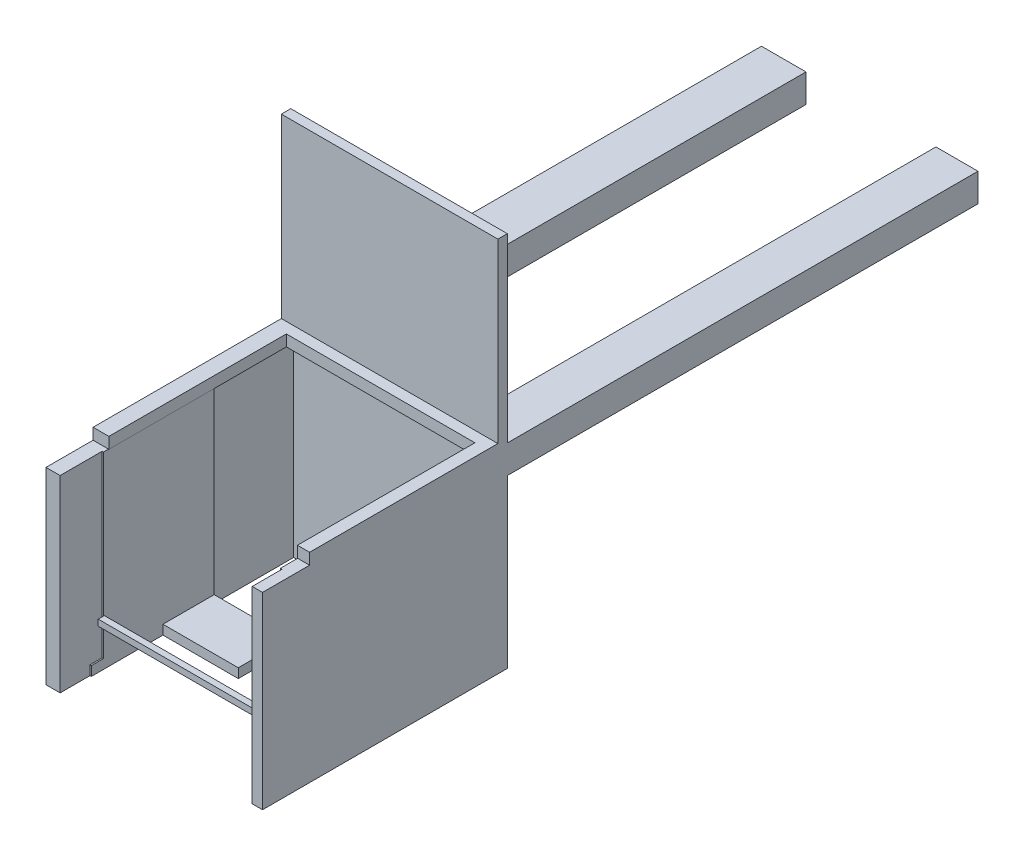
SolidWorks part; units mm, degrees
ref_plane "前视基准面" through (0, 0, 0) normal (0, 0, 1) x (1, 0, 0)
ref_plane "上视基准面" through (0, 0, 0) normal (0, 1, 0) x (1, 0, 0)
ref_plane "右视基准面" through (0, 0, 0) normal (1, 0, 0) x (0, 0, -1)
sketch "草图1" plane through (0, 0, 0) normal (1, 0, 0) x (0, 0, -1)
  line L1 (79.0349, 50.7103) -> (69.0349, 50.7103)
  line L2 (79.0349, 50.7103) -> (79.0349, -149.2897)
  line L3 (79.0349, -149.2897) -> (69.0349, -149.2897)
  line L4 (69.0349, 50.7103) -> (69.0349, -149.2897)
extrude "凸台-拉伸1" add sketch "草图1" along normal blind 230
ref_plane "基准面1" through (0, -149.2897, -69.0349) normal (-1, 0, 0) x (0, 0, 1)
sketch "草图3" plane through (0, -149.2897, 0) normal (0, -1, 0) x (1, 0, 0)
  line L0 (0, -5.7849) -> (0, -132.2849) construction
  line L1 (0, -69.0349) -> (230, -69.0349)
  line L2 (0, -69.0349) -> (0, -79.0349)
  line L3 (0, -79.0349) -> (230, -79.0349)
  line L4 (230, -69.0349) -> (230, -79.0349)
  line L5 (230, -69.0349) -> (0, -69.0349) construction
extrude "凸台-拉伸2" add sketch "草图3" along normal blind 200
sketch "草图4" plane through (0, 0, -69.0349) normal (0, 0, 1) x (1, 0, 0)
  line L0 (230, 50.7103) -> (230, -349.2897) construction
  line L1 (0, -349.2897) -> (230, -349.2897)
  line L2 (0, -349.2897) -> (0, -149.2897)
  line L3 (0, -149.2897) -> (230, -149.2897)
  line L4 (230, -349.2897) -> (230, -149.2897)
extrude "凸台-拉伸3" add sketch "草图4" along normal blind 250
sketch "草图5" plane through (0, 0, -79.0349) normal (0, 0, -1) x (-1, 0, 0)
  line L0 (0, -349.2897) -> (0, 50.7103) construction
  line L1 (0, -82.9101) -> (-39.1073, -82.9101)
  line L2 (0, -82.9101) -> (0, -111.4309)
  line L3 (0, -111.4309) -> (-39.1073, -111.4309)
  line L4 (-39.1073, -82.9101) -> (-39.1073, -111.4309)
extrude "凸台-拉伸4" add sketch "草图5" along normal blind 600
sketch "草图6" plane through (0, 0, -79.0349) normal (0, 0, -1) x (-1, 0, 0)
  line L0 (-230, -349.2897) -> (-230, 50.7103) construction
  line L1 (-230, -76.5576) -> (-187.053, -76.5576)
  line L2 (-230, -76.5576) -> (-230, -101.8503)
  line L3 (-230, -101.8503) -> (-187.053, -101.8503)
  line L4 (-187.053, -76.5576) -> (-187.053, -101.8503)
extrude "凸台-拉伸5" add sketch "草图6" along normal blind 600
sketch "草图8" plane through (0, -349.2897, 0) normal (0, -1, 0) x (-1, 0, 0)
  line L0 (0, -180.9651) -> (-230, -180.9651) construction
  line L1 (-219.0593, -180.9651) -> (-14.9883, -180.9651)
  line L2 (-219.0593, -180.9651) -> (-219.0593, -149.3194)
  line L3 (-219.0593, -149.3194) -> (-14.9883, -149.3194)
  line L4 (-14.9883, -180.9651) -> (-14.9883, -149.3194)
extrude "切除-拉伸1" cut sketch "草图8" against normal blind 600
sketch "草图9" plane through (0, -349.2897, 0) normal (0, -1, 0) x (-1, 0, 0)
  line L1 (-217.3134, -136.3173) -> (-16.4227, -136.3173)
  line L2 (-217.3134, -136.3173) -> (-217.3134, -73.1682)
  line L3 (-217.3134, -73.1682) -> (-16.4227, -73.1682)
  line L4 (-16.4227, -136.3173) -> (-16.4227, -73.1682)
extrude "切除-拉伸2" cut sketch "草图9" against normal blind 600
sketch "草图10" plane through (0, -349.2897, 0) normal (0, -1, 0) x (1, 0, 0)
  line L1 (216.9562, 18.735) -> (14.4356, 18.735)
  line L2 (216.9562, 18.735) -> (216.9562, -67.7448)
  line L3 (216.9562, -67.7448) -> (14.4356, -67.7448)
  line L4 (14.4356, 18.735) -> (14.4356, -67.7448)
extrude "切除-拉伸3" cut sketch "草图10" against normal blind 600
sketch "草图11" plane through (0, -349.2897, 0) normal (0, -1, 0) x (-1, 0, 0)
  line L0 (-16.4227, -73.1682) -> (-217.3134, -73.1682) construction
  line L1 (-141.4355, -73.1682) -> (-96.4371, -73.1682)
  line L2 (-141.4355, -73.1682) -> (-141.4355, -18.735)
  line L3 (-141.4355, -18.735) -> (-96.4371, -18.735)
  line L4 (-96.4371, -73.1682) -> (-96.4371, -18.735)
  line L5 (-216.9562, -18.735) -> (-14.4356, -18.735) construction
extrude "切除-拉伸4" cut sketch "草图11" against normal blind 600
sketch "草图12" plane through (0, -149.2897, 0) normal (0, 1, 0) x (1, 0, 0)
  line L0 (16.4227, -73.1682) -> (96.4371, -73.1682) construction
  line L1 (96.4371, -18.735) -> (16.4227, -18.735)
  line L2 (96.4371, -18.735) -> (96.4371, -73.1682)
  line L3 (96.4371, -73.1682) -> (16.4227, -73.1682)
  line L4 (16.4227, -18.735) -> (16.4227, -73.1682)
extrude "切除-拉伸6" cut sketch "草图12" against normal blind 190
sketch "草图13" plane through (0, -149.2897, 0) normal (0, 1, 0) x (1, 0, 0)
  line L0 (216.9562, 67.7448) -> (216.9562, -18.735) construction
  line L1 (141.4355, -73.1682) -> (216.9562, -73.1682)
  line L2 (141.4355, -73.1682) -> (141.4355, -18.735)
  line L3 (141.4355, -18.735) -> (216.9562, -18.735)
  line L4 (216.9562, -73.1682) -> (216.9562, -18.735)
  line L5 (216.9562, -18.735) -> (141.4355, -18.735) construction
extrude "切除-拉伸7" cut sketch "草图13" against normal blind 190
sketch "草图14" plane through (0, -149.2897, 0) normal (0, 1, 0) x (1, 0, 0)
  line L1 (14.9883, -149.3194) -> (217.3134, -149.3194)
  line L2 (14.9883, -149.3194) -> (14.9883, -136.3173)
  line L3 (14.9883, -136.3173) -> (217.3134, -136.3173)
  line L4 (217.3134, -149.3194) -> (217.3134, -136.3173)
extrude "切除-拉伸8" cut sketch "草图14" against normal blind 190
sketch "草图15" plane through (0, 0, -69.0349) normal (0, 0, 1) x (1, 0, 0)
  line L1 (230, -149.2897) -> (0, -149.2897)
  line L2 (230, -149.2897) -> (230, -137.384)
  line L3 (230, -137.384) -> (0, -137.384)
  line L4 (0, -149.2897) -> (0, -137.384)
extrude "凸台-拉伸6" add sketch "草图15" along normal blind 200
sketch "草图16" plane through (0, -149.2897, 0) normal (0, -1, 0) x (1, 0, 0)
  line L0 (16.4227, 130.9651) -> (217.3134, 130.9651) construction
  line L1 (16.7772, 130.9651) -> (217.0839, 130.9651)
  line L2 (16.7772, 130.9651) -> (16.7772, -57.5549)
  line L3 (16.7772, -57.5549) -> (217.0839, -57.5549)
  line L4 (217.0839, 130.9651) -> (217.0839, -57.5549)
extrude "切除-拉伸9" cut sketch "草图16" against normal blind 50
sketch "草图17" plane through (0, -349.2897, 0) normal (0, -1, 0) x (1, 0, 0)
  line L1 (219.0593, 149.3194) -> (16.4227, 149.3194)
  line L2 (219.0593, 149.3194) -> (219.0593, 136.3173)
  line L3 (219.0593, 136.3173) -> (16.4227, 136.3173)
  line L4 (16.4227, 149.3194) -> (16.4227, 136.3173)
extrude "切除-拉伸10" cut sketch "草图17" against normal blind 50
sketch "草图18" plane through (217.3134, 0, 0) normal (-1, 0, 0) x (0, 0, 1)
  line L1 (136.3173, -299.2897) -> (136.3173, -349.2897) construction
  line L2 (136.3173, -305.7908) -> (142.8183, -305.7908)
  line L3 (136.3173, -305.7908) -> (136.3173, -299.2897)
  line L4 (136.3173, -299.2897) -> (142.8183, -299.2897)
  line L5 (142.8183, -305.7908) -> (142.8183, -299.2897)
  line L6 (136.3173, -299.2897) -> (149.3194, -299.2897) construction
extrude "凸台-拉伸9" add sketch "草图18" along normal blind 200 separate body
sketch "草图19" plane through (0, -82.9101, 0) normal (0, 1, 0) x (1, 0, 0)
  line L0 (0, 679.0349) -> (0, 79.0349) construction
  line L1 (39.1073, 679.0349) -> (0, 679.0349)
  line L2 (39.1073, 679.0349) -> (39.1073, 629.0349)
  line L3 (39.1073, 629.0349) -> (0, 629.0349)
  line L4 (0, 679.0349) -> (0, 629.0349)
extrude "切除-拉伸11" cut sketch "草图19" against normal blind 1000
sketch "草图20" plane through (0, -76.5576, 0) normal (0, 1, 0) x (1, 0, 0)
  line L0 (230, 679.0349) -> (230, 79.0349) construction
  line L1 (187.053, 679.0349) -> (230, 679.0349)
  line L2 (187.053, 679.0349) -> (187.053, 629.0349)
  line L3 (187.053, 629.0349) -> (230, 629.0349)
  line L4 (230, 679.0349) -> (230, 629.0349)
extrude "切除-拉伸12" cut sketch "草图20" against normal blind 1000
sketch "草图21" plane through (0, -82.9101, 0) normal (0, 1, 0) x (1, 0, 0)
  line L0 (39.1073, 629.0349) -> (39.1073, 79.0349) construction
  line L1 (0, 629.0349) -> (39.1073, 629.0349)
  line L2 (0, 629.0349) -> (0, 579.0349)
  line L3 (0, 579.0349) -> (39.1073, 579.0349)
  line L4 (39.1073, 629.0349) -> (39.1073, 579.0349)
extrude "切除-拉伸13" cut sketch "草图21" against normal blind 1000
sketch "草图22" plane through (0, -76.5576, 0) normal (0, 1, 0) x (1, 0, 0)
  line L0 (230, 629.0349) -> (230, 79.0349) construction
  line L1 (187.053, 629.0349) -> (230, 629.0349)
  line L2 (187.053, 629.0349) -> (187.053, 579.0349)
  line L3 (187.053, 579.0349) -> (230, 579.0349)
  line L4 (230, 629.0349) -> (230, 579.0349)
extrude "切除-拉伸14" cut sketch "草图22" against normal blind 1000
sketch "草图23" plane through (0, 0, -579.0349) normal (0, 0, -1) x (-1, 0, 0)
  line L1 (0, -111.4309) -> (-39.1073, -111.4309)
  line L2 (0, -111.4309) -> (0, -82.9101)
  line L3 (0, -82.9101) -> (-39.1073, -82.9101)
  line L4 (-39.1073, -111.4309) -> (-39.1073, -82.9101)
extrude "切除-拉伸15" cut sketch "草图23" against normal blind 500
sketch "草图24" plane through (0, 0, -579.0349) normal (0, 0, -1) x (-1, 0, 0)
  line L0 (-230, -101.8503) -> (-230, -76.5576) construction
  line L1 (-187.053, -101.8503) -> (-230, -101.8503)
  line L2 (-187.053, -101.8503) -> (-187.053, -76.5576)
  line L3 (-187.053, -76.5576) -> (-230, -76.5576)
  line L4 (-230, -101.8503) -> (-230, -76.5576)
  line L5 (-187.053, -76.5576) -> (-230, -76.5576) construction
extrude "切除-拉伸16" cut sketch "草图24" against normal blind 500
sketch "草图25" plane through (0, 0, -79.0349) normal (0, 0, -1) x (-1, 0, 0)
  line L0 (-230, -349.2897) -> (-230, 50.7103) construction
  line L1 (-230, -141.8439) -> (-185.3, -141.8439)
  line L2 (-230, -141.8439) -> (-230, -171.8439)
  line L3 (-230, -171.8439) -> (-185.3, -171.8439)
  line L4 (-185.3, -141.8439) -> (-185.3, -171.8439)
  line L5 (0, -349.2897) -> (0, 50.7103) construction
  line L6 (0, -141.8439) -> (-47.2867, -141.8439)
  line L7 (0, -141.8439) -> (0, -171.8439)
  line L8 (0, -171.8439) -> (-47.2867, -171.8439)
  line L9 (-47.2867, -141.8439) -> (-47.2867, -171.8439)
extrude "凸台-拉伸10" add sketch "草图25" along normal blind 500
